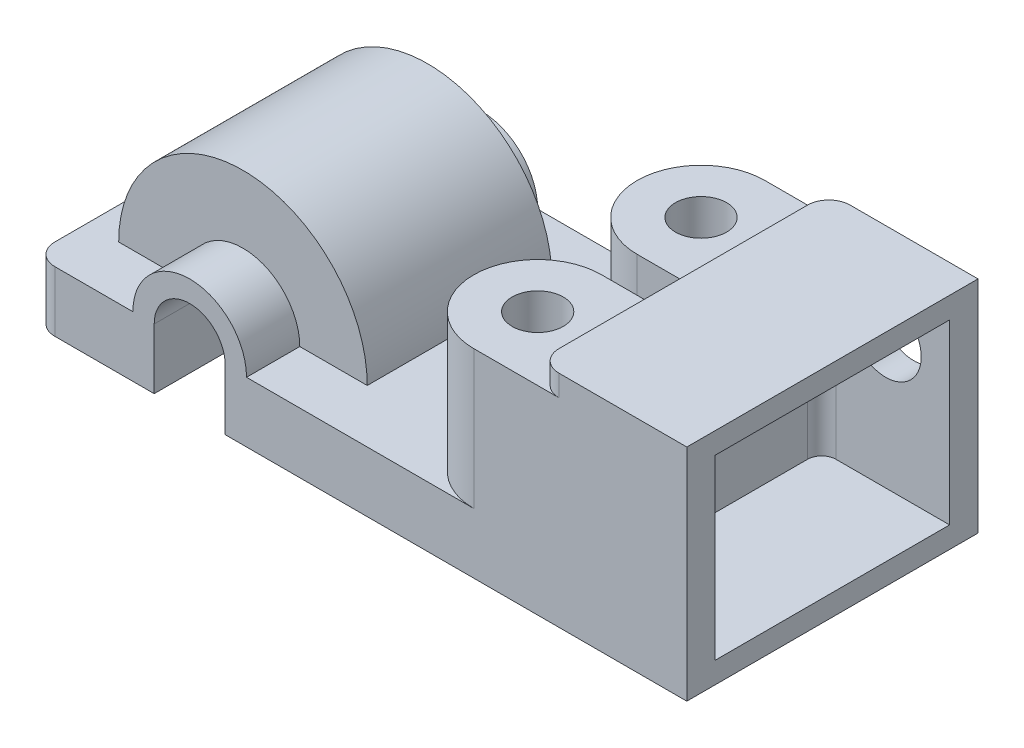
SolidWorks part; units mm, degrees
ref_plane "Front Plane" through (0, 0, 0) normal (0, 0, 1) x (1, 0, 0)
ref_plane "Top Plane" through (0, 0, 0) normal (0, 1, 0) x (1, 0, 0)
ref_plane "Right Plane" through (0, 0, 0) normal (1, 0, 0) x (0, 0, -1)
sketch "Sketch1" plane through (0, 0, 0) normal (0, 0, 1) x (1, 0, 0)
  line L0 (-68.3049, -15.9808) -> (115.6951, -15.9808)
  line L1 (115.6951, -15.9808) -> (115.6951, 46.0192)
  line L2 (115.6951, 46.0192) -> (73.6951, 46.0192)
  line L3 (73.6951, 46.0192) -> (73.6951, 1.0192)
  line L4 (73.6951, 1.0192) -> (-68.3049, 1.0192)
  line L5 (-68.3049, 1.0192) -> (-68.3049, -15.9808)
extrude "Boss-Extrude1" add sketch "Sketch1" along normal blind 82
sketch "Sketch2" plane through (115.6951, 0, 0) normal (1, 0, 0) x (0, 0, -1)
  line L0 (-82, -15.9808) -> (-82, 46.0192) construction
  line L1 (-74, 40.0192) -> (-8, 40.0192)
  line L2 (-74, 40.0192) -> (-74, -9.9808)
  line L3 (-74, -9.9808) -> (-8, -9.9808)
  line L4 (-8, 40.0192) -> (-8, -9.9808)
  line L5 (-82, 46.0192) -> (0, 46.0192) construction
  line L6 (-82, -15.9808) -> (0, -15.9808) construction
  line L7 (0, -15.9808) -> (0, 46.0192) construction
  dimension "D1" = 8
  dimension "D2" = 6
  dimension "D3" = 6
  dimension "D4" = 8
extrude "Cut-Extrude1" cut sketch "Sketch2" against normal blind 36
sketch "Sketch3" plane through (0, 0, 0) normal (0, 0, -1) x (-1, 0, 0)
  line L0 (-115.6951, -15.9808) -> (-115.6951, 46.0192) construction
  line L1 (68.3049, -15.9808) -> (-115.6951, -15.9808) construction
  circle A0 centre (-97.6951, 27.0192) radius 10
  dimension "D1" = 18
  dimension "D2" = 43
extrude "Cut-Extrude2" cut sketch "Sketch3" against normal blind 36
sketch "Sketch4" plane through (0, 1.0192, 0) normal (0, 1, 0) x (1, 0, 0)
  line L0 (73.6951, -41) -> (-68.3049, -41) construction
  line L1 (-68.3049, -82) -> (-68.3049, 0) construction
  line L4 (55.6951, -46) -> (73.6951, -46)
  line L5 (73.6951, -82) -> (73.6951, 0) construction
  line L6 (73.6951, -46) -> (73.6951, -82)
  line L7 (73.6951, -82) -> (-68.3049, -82) construction
  line L8 (73.6951, -82) -> (55.6951, -82)
  arc A0 (55.6951, -46) -> (55.6951, -82) centre (55.6951, -64) ccw
extrude "Boss-Extrude6" add sketch "Sketch4" along normal blind 39
sketch "Sketch5" plane through (0, 40.0192, 0) normal (0, 1, 0) x (1, 0, 0)
  circle A0 centre (55.6951, -64) radius 7.2
extrude "Cut-Extrude3" cut sketch "Sketch5" against normal blind 27
cosmetic thread "Cosmetic Thread1" parameters "D1"=24, "D2"=18
ref_plane "Plane1" through (0, 0, 41) normal (0, 0, 1) x (1, 0, 0)
mirror "Mirror3" about plane through (0, 0, 41) normal (0, 0, 1) of "Boss-Extrude6", "Cut-Extrude3"
cosmetic thread "Cosmetic Thread2" parameters "D1"=24, "D2"=18
sketch "Sketch7" plane through (0, 1.0192, 0) normal (0, 1, 0) x (1, 0, 0)
  line L0 (-24.3049, 0) -> (-24.3049, -82)
  line L1 (55.6951, 0) -> (-68.3049, 0) construction
  line L2 (55.6951, -82) -> (-68.3049, -82) construction
  line L3 (115.6951, -82) -> (115.6951, 0) construction
  line L4 (-24.3049, -82) -> (-8.3049, -82)
  line L5 (-8.3049, -82) -> (-8.3049, -67)
  line L6 (-8.3049, -67) -> (10.6951, -67)
  line L7 (10.6951, -67) -> (10.6951, -15)
  line L8 (10.6951, -15) -> (-8.3049, -15)
  line L9 (-8.3049, -15) -> (-8.3049, 0)
  line L10 (-8.3049, 0) -> (-24.3049, 0)
  dimension "D1" = 140
revolve "Revolve2" add sketch "Sketch7" angle 180 about L0
sketch "Sketch8" plane through (0, 0, 82) normal (0, 0, 1) x (1, 0, 0)
  line L0 (-8.3049, 1.0192) -> (-24.3049, 1.0192) construction
  line L1 (-24.3049, 1.0192) -> (-8.3049, 1.0192) construction
  line L2 (-14.3049, 1.0192) -> (-14.3049, -15.9808)
  line L3 (-68.3049, -15.9808) -> (115.6951, -15.9808) construction
  line L4 (-14.3049, -15.9808) -> (-34.3049, -15.9808)
  line L5 (-34.3049, -15.9808) -> (-34.3049, 1.0192)
  arc A0 (-14.3049, 1.0192) -> (-34.3049, 1.0192) centre (-24.3049, 1.0192) ccw
extrude "Cut-Extrude4" cut sketch "Sketch8" against normal blind 153
sketch "Sketch10" plane through (0, -15.9808, 0) normal (0, -1, 0) x (1, 0, 0)
  line L4 (-51.3049, 59) -> (2.6951, 59)
  line L5 (2.6951, 59) -> (2.6951, 23)
  line L6 (2.6951, 23) -> (-51.3049, 23)
  line L7 (-51.3049, 23) -> (-51.3049, 59)
extrude "Cut-Extrude5" cut sketch "Sketch10" against normal blind 17
sketch "Sketch11" plane through (0, 1.0192, 0) normal (0, -1, 0) x (1, 0, 0)
  line L1 (-24.3049, 0) -> (-24.3049, 82) construction
  line L2 (34.1, 41) -> (-34.1, 41) construction
  line L3 (2.6951, 41) -> (2.6951, 59)
  line L4 (2.6951, 59) -> (-24.3049, 59)
  line L5 (2.6951, 59) -> (2.6951, 23)
  line L6 (2.6951, 23) -> (-24.3049, 23)
revolve "Cut-Revolve2" cut sketch "Sketch11" angle 180 about L0
fillet "Fillet1" radius 4 2 edges at (79.6951, 15.0192, 8) (79.6951, 15.0192, 74)
fillet "Fillet2" radius 6 4 edges at (73.6951, 43.0192, 82) (73.6951, 43.0192, 0) (-68.3049, -7.4808, 0) (-68.3049, -7.4808, 82)
